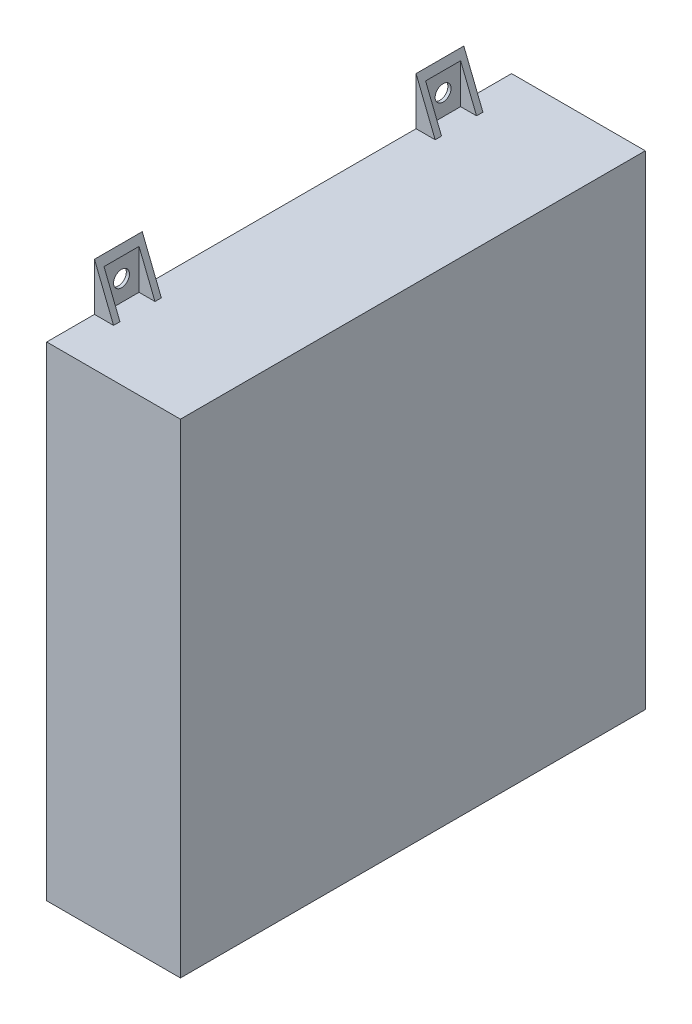
SolidWorks part; units mm, degrees
ref_plane "前视基准面" through (0, 0, 0) normal (0, 0, 1) x (1, 0, 0)
ref_plane "上视基准面" through (0, 0, 0) normal (0, 1, 0) x (1, 0, 0)
ref_plane "右视基准面" through (0, 0, 0) normal (1, 0, 0) x (0, 0, -1)
sketch "草图1" plane through (0, 0, 0) normal (1, 0, 0) x (0, 0, -1)
  line L1 (-73, 76) -> (73, 76)
  line L2 (-73, 76) -> (-73, -76)
  line L3 (-73, -76) -> (73, -76)
  line L4 (73, 76) -> (73, -76)
  dimension "D1" = 152
  dimension "D2" = 146
  dimension "D3" = 76
  dimension "D4" = 73
extrude "凸台-拉伸1" add sketch "草图1" along normal blind 42
ref_plane "基准面1" through (0, 0, 58) normal (0, 0, 1) x (1, 0, 0)
sketch "草图2" plane through (0, 0, 58) normal (0, 0, 1) x (1, 0, 0)
  line L0 (0, -76) -> (0, -91)
  line L1 (0, -91) -> (6, -76)
  line L2 (42, -76) -> (0, -76) construction
  line L3 (6, -76) -> (0, -76)
  dimension "D1" = 15
  dimension "D2" = 6
extrude "凸台-拉伸2" add sketch "草图2" against normal blind 15
ref_plane "基准面2" through (0, 0, 0) normal (0, 0, -1) x (-1, 0, 0)
ref_plane "基准面3" through (0, 0, 0) normal (0, -1, 0) x (-1, 0, 0)
mirror "镜向1" about plane through (0, 0, 0) normal (0, -1, 0) of "凸台-拉伸2"
mirror "镜向2" about plane through (0, 0, 0) normal (0, 0, -1) of "镜向1", "凸台-拉伸2"
sketch "草图3" plane through (0, 0, 58) normal (0, 0, 1) x (1, 0, 0)
  line L0 (6, -76) -> (1, -88.5)
  line L1 (0, -91) -> (6, -76) construction
  line L2 (1, -88.5) -> (1, -76)
  line L3 (6, -76) -> (0, -76) construction
  line L4 (1, -76) -> (6, -76)
  dimension "D1" = 5
extrude "切除-拉伸1" cut sketch "草图3" against normal blind 11 from offset 2 offset against normal yes
mirror "镜向3" about plane through (0, 0, 0) normal (0, 0, -1) of "切除-拉伸1"
mirror "镜向4" about plane through (0, 0, 0) normal (0, -1, 0) of "镜向3", "切除-拉伸1"
sketch "草图4" plane through (1, 0, 0) normal (1, 0, 0) x (0, 0, -1)
  line L1 (-45, -76) -> (-45, -88.5) construction
  line L2 (0, 0) -> (0, -50000) construction
  line L3 (0, 0) -> (50000, 0) construction
  circle A0 centre (-50.5, -82.5) radius 2.5
  circle A1 centre (50.5, -82.5) radius 2.5
  circle A2 centre (-50.5, 82.5) radius 2.5
  circle A3 centre (50.5, 82.5) radius 2.5
  dimension "D1" = 5
  dimension "D2" = 82.5
  dimension "D3" = 5.5
extrude "切除-拉伸2" cut sketch "草图4" against normal blind 11
